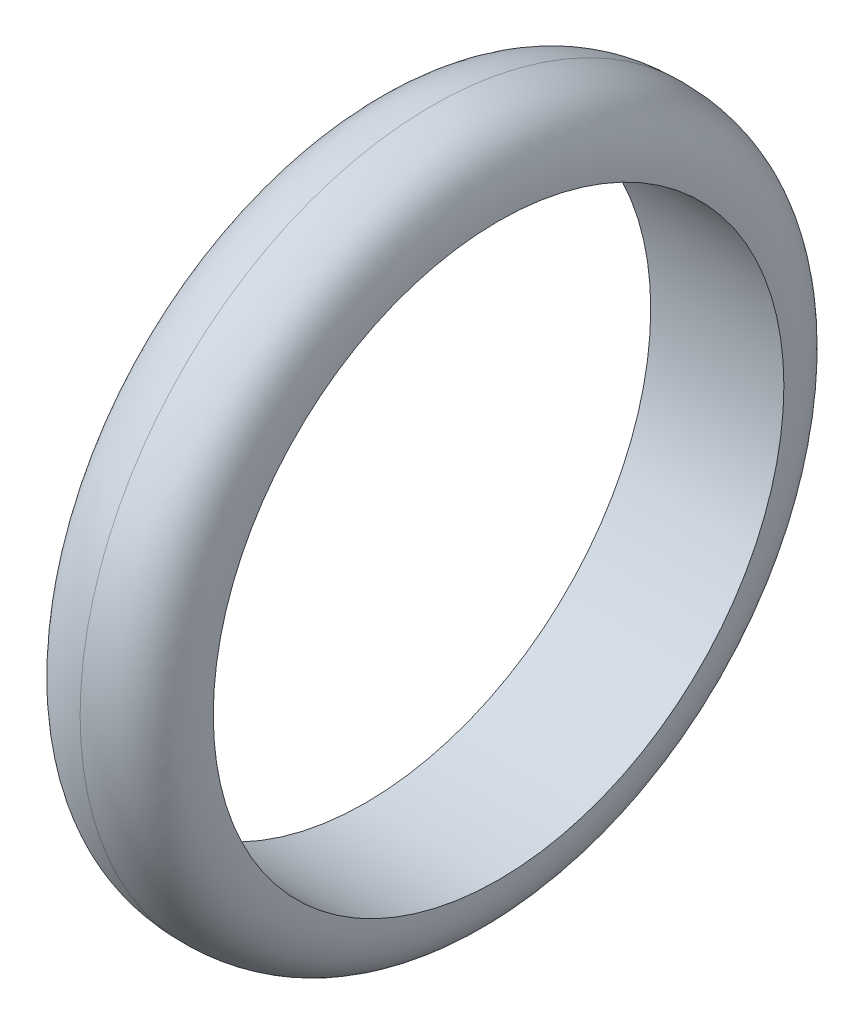
SolidWorks part; units mm, degrees
ref_plane "Front Plane" through (0, 0, 0) normal (0, 0, 1) x (1, 0, 0)
ref_plane "Top Plane" through (0, 0, 0) normal (0, 1, 0) x (1, 0, 0)
ref_plane "Right Plane" through (0, 0, 0) normal (1, 0, 0) x (0, 0, -1)
sketch "Sketch1" plane through (0, 0, 0) normal (0, 0, 1) x (1, 0, 0)
  line L0 (-8.89, 38.1) -> (8.89, 38.1)
  line L1 (0, 0) -> (0, 4.1835) construction
  line L2 (8.89, 38.1) -> (8.89, 46.99) construction
  line L3 (8.89, 46.99) -> (0, 46.99) construction
  line L4 (-8.89, 38.1) -> (-8.89, 46.99) construction
  line L5 (-8.89, 46.99) -> (0, 46.99) construction
  line L6 (0, 0) -> (39.6195, 0) construction
  spline S0 degree 2 poles (8.89, 38.1) (8.89, 46.99) (0, 46.99) knots 0 0 0 1 1 1
  spline S1 degree 2 poles (-8.89, 38.1) (-8.89, 46.99) (0, 46.99) knots 0 0 0 1 1 1
  dimension "D1" = 17.78
  dimension "D2" = 38.1
  dimension "D3" = 8.89
revolve "Revolve1" add sketch "Sketch1" angle 360 about L6
